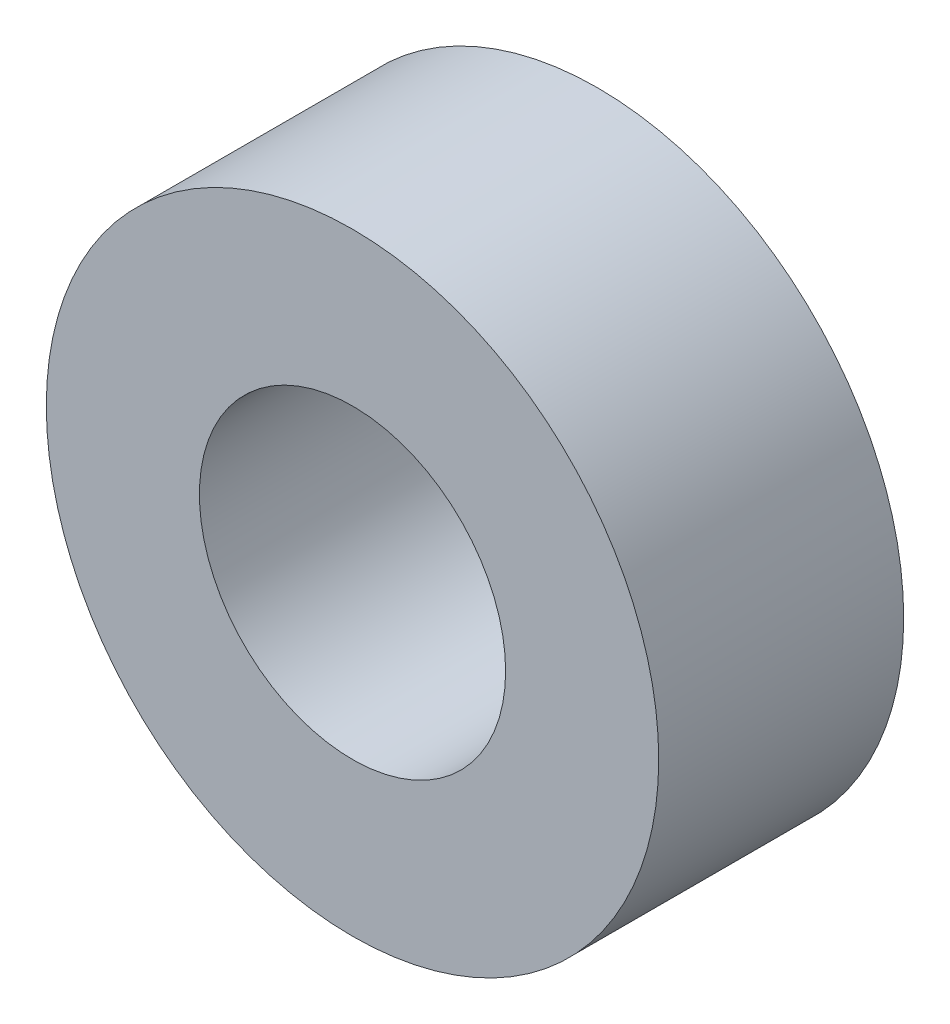
SolidWorks part; units mm, degrees
material "ABS"
ref_plane "Спереди" through (0, 0, 0) normal (0, 0, 1) x (1, 0, 0)
ref_plane "Сверху" through (0, 0, 0) normal (0, 1, 0) x (1, 0, 0)
ref_plane "Справа" through (0, 0, 0) normal (1, 0, 0) x (0, 0, -1)
sketch "Эскиз1" plane through (0, 0, 0) normal (0, 0, 1) x (1, 0, 0)
  circle A0 centre (0, 0) radius 1.25
  circle A1 centre (0, 0) radius 2.5
  dimension "D1" = 2.5
  dimension "D2" = 5
extrude "Бобышка-Вытянуть1" add sketch "Эскиз1" along normal blind 2
